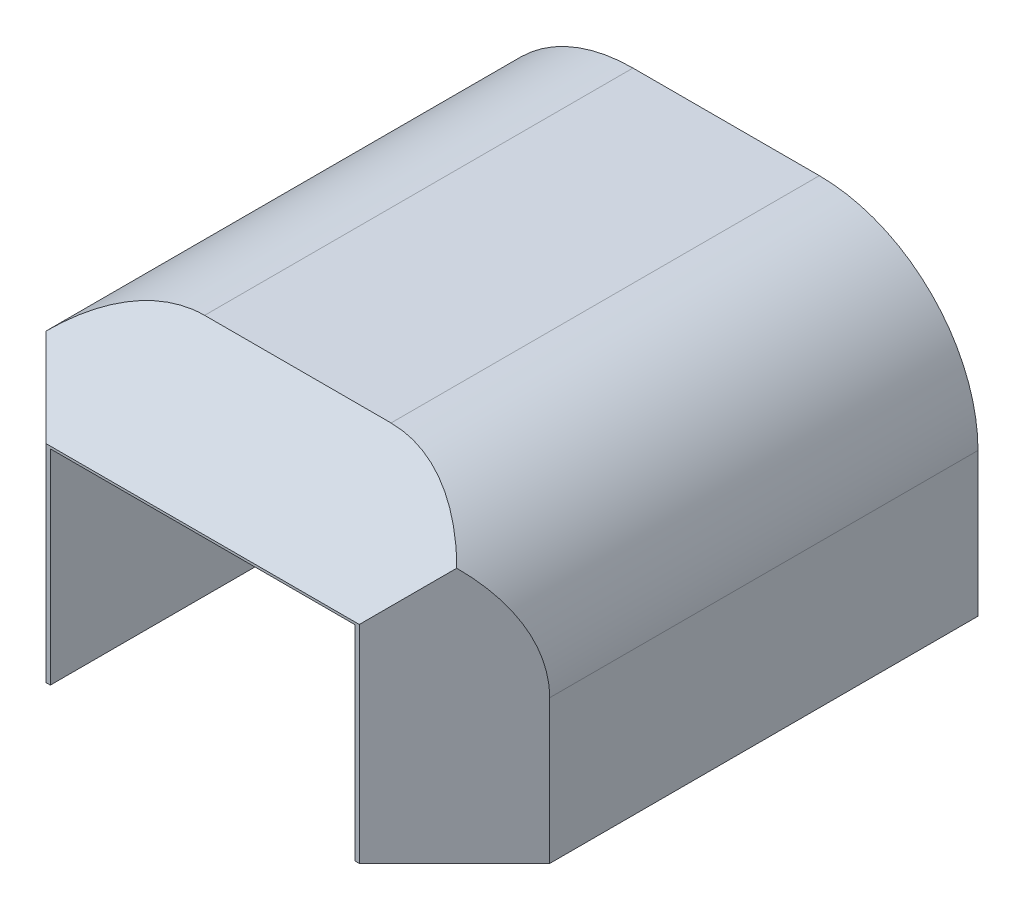
SolidWorks part; units mm, degrees
ref_plane "Front Plane" through (0, 0, 0) normal (0, 0, 1) x (1, 0, 0)
ref_plane "Top Plane" through (0, 0, 0) normal (0, 1, 0) x (1, 0, 0)
ref_plane "Right Plane" through (0, 0, 0) normal (1, 0, 0) x (0, 0, -1)
sketch "Sketch1" plane through (0, 0, 0) normal (0, 0, 1) x (1, 0, 0)
  line L0 (0, 0) -> (-9.6, 0)
  line L1 (-9.6, 0) -> (-9.6, 12.9)
  line L2 (-9.6, 12.9) -> (9.6, 12.9)
  line L3 (9.6, 12.9) -> (9.6, 0)
  line L4 (9.6, 0) -> (0, 0)
  line L5 (-9.6, 0) -> (-15.875, 0)
  line L6 (-15.875, 0) -> (-15.875, 19.05)
  line L7 (-15.875, 19.05) -> (15.875, 19.05)
  line L8 (15.875, 19.05) -> (15.875, 0)
  line L9 (15.875, 0) -> (9.6, 0)
  dimension "D1" = 19.2
  dimension "D2" = 12.9
  dimension "D3" = 19.05
  dimension "D4" = 31.75
extrude "Boss-Extrude1" add sketch "Sketch1" along normal mid plane 33 contours L9 L8 L7 L6 L5 L1 L2 L3
chamfer "Chamfer1" distance 6 angle 45 3 edges at (-15.875, 9.525, 16.5) (15.875, 9.525, 16.5) (0, 19.05, 16.5)
fillet "Fillet1" radius 10 2 edges at (15.875, 19.05, -3) (-15.875, 19.05, -3)
